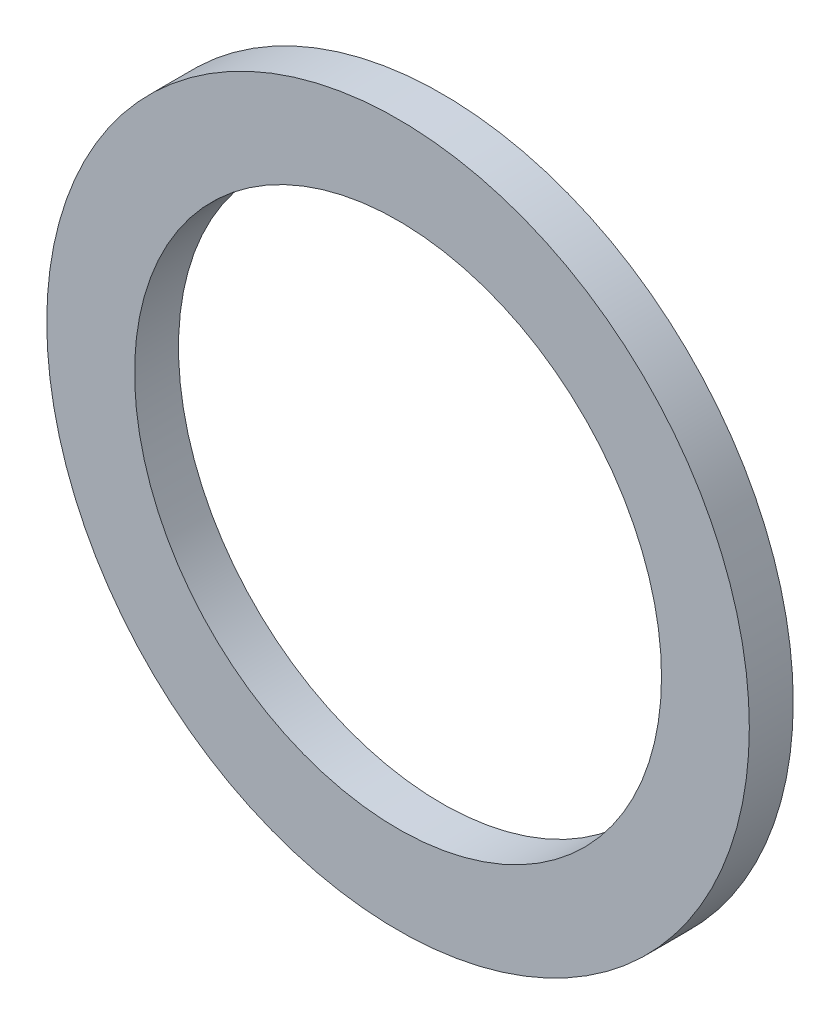
SolidWorks part; units mm, degrees
ref_plane "Front Plane" through (0, 0, 0) normal (0, 0, 1) x (1, 0, 0)
ref_plane "Top Plane" through (0, 0, 0) normal (0, 1, 0) x (1, 0, 0)
ref_plane "Right Plane" through (0, 0, 0) normal (1, 0, 0) x (0, 0, -1)
sketch "Sketch1" plane through (0, 0, 0) normal (0, 0, 1) x (1, 0, 0)
  circle A0 centre (0, 0) radius 20
  circle A1 centre (0, 0) radius 15
  dimension "D1" = 40
  dimension "D2" = 30
extrude "Boss-Extrude1" add sketch "Sketch1" along normal blind 2.5
